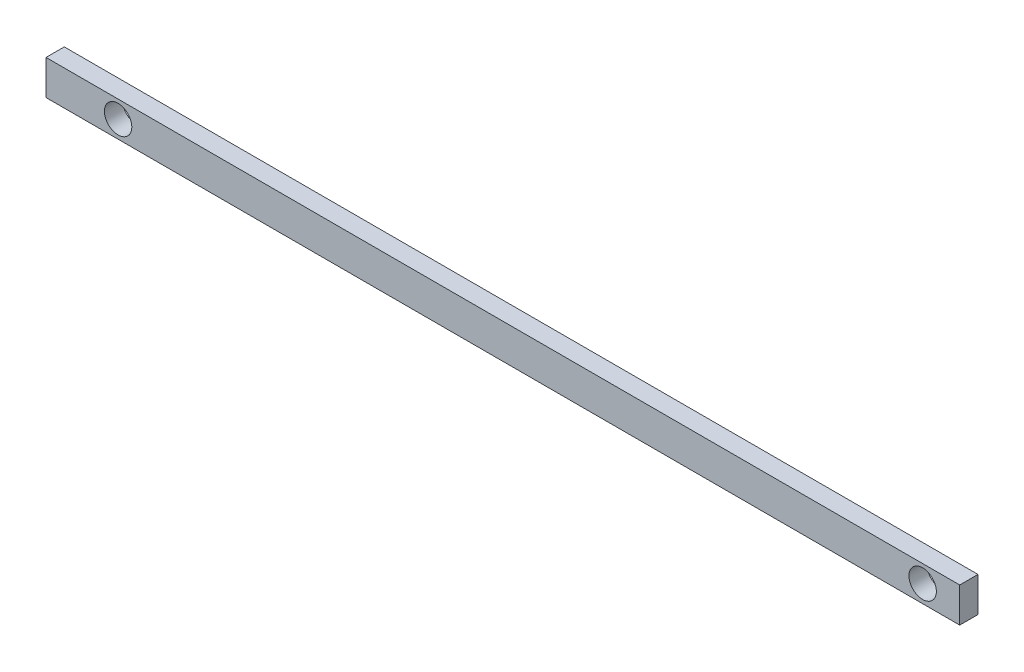
SolidWorks part; units mm, degrees
ref_plane "Front Plane" through (0, 0, 0) normal (0, 0, 1) x (1, 0, 0)
ref_plane "Top Plane" through (0, 0, 0) normal (0, 1, 0) x (1, 0, 0)
ref_plane "Right Plane" through (0, 0, 0) normal (1, 0, 0) x (0, 0, -1)
sketch "Sketch1" plane through (0, 0, 0) normal (0, 0, 1) x (1, 0, 0)
  line L0 (-435.9137, 0) -> (413.7056, 0) construction
  line L1 (0, 221.4467) -> (0, -243.0203) construction
  line L3 (-250, 9.5178) -> (250, 9.5178)
  line L4 (-250, 9.5178) -> (-250, -9.5178)
  line L5 (-250, -9.5178) -> (250, -9.5178)
  line L6 (250, 9.5178) -> (250, -9.5178)
  line L7 (-250, 9.5178) -> (250, -9.5178) construction
  line L8 (-250, -9.5178) -> (250, 9.5178) construction
  circle A0 centre (-210.5495, 0) radius 7.5
  circle A1 centre (229.7085, 0) radius 7.5
  point P5 (0, 0)
  dimension "D2" = 15
  dimension "D3" = 15
  dimension "D1" = 500
  dimension "D4" = 440.258
extrude "Boss-Extrude1" add sketch "Sketch1" along normal blind 10
